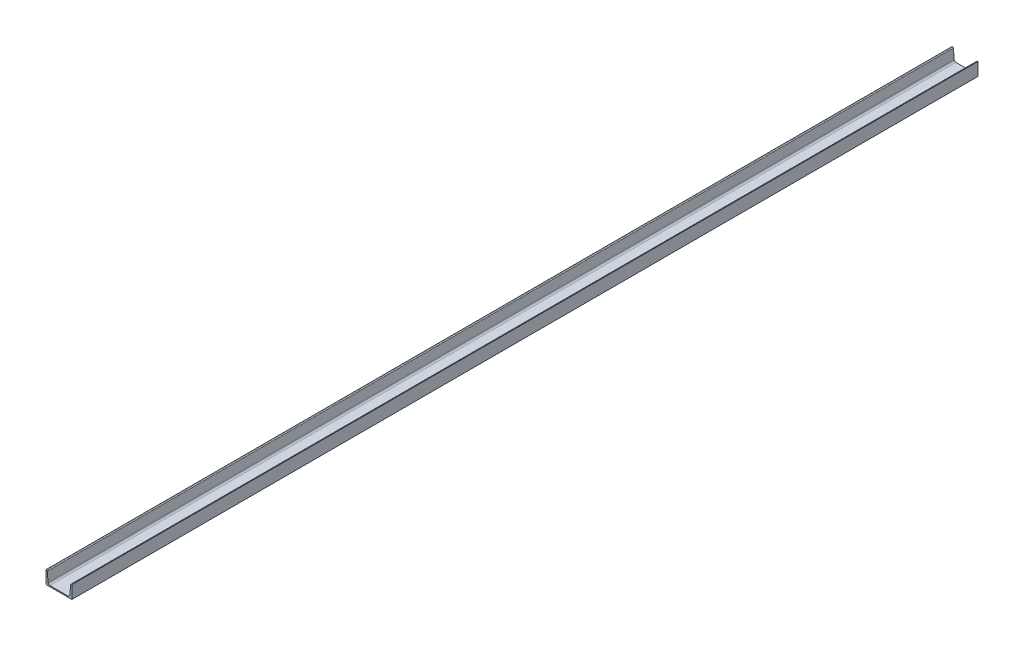
SolidWorks part; units mm, degrees
ref_plane "Front Plane" through (0, 0, 0) normal (0, 0, 1) x (1, 0, 0)
ref_plane "Top Plane" through (0, 0, 0) normal (0, 1, 0) x (1, 0, 0)
ref_plane "Right Plane" through (0, 0, 0) normal (1, 0, 0) x (0, 0, -1)
sketch "Sketch21" plane through (0, 0, 0) normal (1, 0, 0) x (0, 0, -1)
  line L0 (0, 0) -> (5250, 0)
  dimension "D1" = 5250
other "C channel C 150 X 75 X 6.5(1)"
ref_plane "Plane2" through (0, 0, 0) normal (0, 0, -1) x (0, 1, 0)
sketch "Sketch1" plane through (0, 0, 0) normal (0, 0, -1) x (0, 1, 0)
  line L0 (75, 150) -> (0, 150)
  line L1 (75, 0) -> (0, 0)
  line L2 (0, 150) -> (0, 0)
  line L5 (0, 10) -> (40.75, 10) construction
  line L6 (75, 150) -> (75, 147.5781)
  line L7 (75, 0) -> (75, 2.4219)
  line L8 (6.5, 75) -> (0, 75) construction
  line L12 (6.5, 127.8402) -> (6.5, 22.1598)
  line L17 (15.6284, 137.8021) -> (70.4358, 142.5972)
  line L18 (15.6284, 12.1979) -> (70.4358, 7.4028)
  arc A0 (70.4358, 142.5972) -> (75, 147.5781) centre (70, 147.5781) ccw
  arc A1 (70.4358, 7.4028) -> (75, 2.4219) centre (70, 2.4219) cw
  arc A9 (6.5, 22.1598) -> (15.6284, 12.1979) centre (16.5, 22.1598) ccw
  arc A10 (6.5, 127.8402) -> (15.6284, 137.8021) centre (16.5, 127.8402) cw
  point P10 (37.5, 150)
  point P11 (37.5, 0)
  point P14 (3.25, 75)
  point P15 (0, 0)
  dimension "D4" = 34.25
  dimension "RI" = 10
  dimension "D2" = 5
  dimension "RA" = 5
  dimension "Depth" = 150
  dimension "BF" = 75
  dimension "TW" = 6.5
  dimension "TF" = 10
